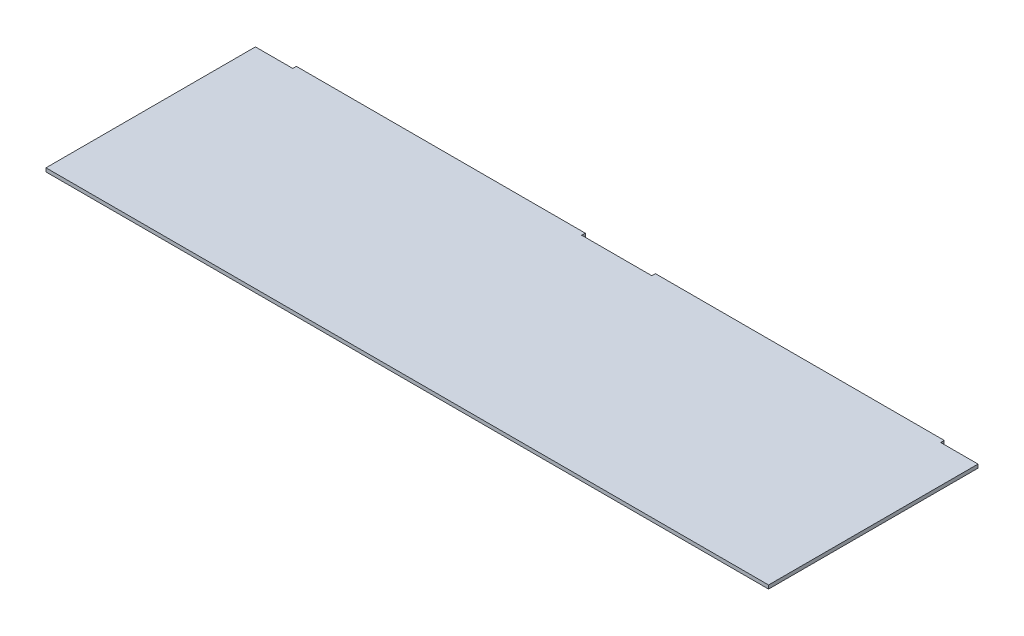
SolidWorks part; units mm, degrees
material "6061-T6 (SS)"
ref_plane "X-Y Datum" through (0, 0, 0) normal (0, 0, 1) x (1, 0, 0)
ref_plane "X-Z Datum" through (0, 0, 0) normal (0, 1, 0) x (1, 0, 0)
ref_plane "Y-Z Datum" through (0, 0, 0) normal (1, 0, 0) x (0, 0, -1)
sketch "Sketch1" plane through (0, 0, 0) normal (0, 1, 0) x (1, 0, 0)
  line L1 (-317.6778, 92.075) -> (317.6778, 92.075)
  line L2 (-317.6778, 92.075) -> (-317.6778, -92.075)
  line L3 (-317.6778, -92.075) -> (317.6778, -92.075)
  line L4 (317.6778, 92.075) -> (317.6778, -92.075)
  line L5 (-317.6778, 92.075) -> (317.6778, -92.075) construction
  line L6 (-317.6778, -92.075) -> (317.6778, 92.075) construction
  point P0 (0, 0)
  dimension "D1" = 635.3556
  dimension "D2" = 184.15
extrude "Boss-Extrude1" add sketch "Sketch1" along normal mid plane 3.175
sketch "Sketch2" plane through (0, 0, -92.075) normal (0, 0, -1) x (-1, 0, 0)
  line L20 (-317.6778, -1.5875) -> (317.6778, -1.5875) construction
  line L21 (-284.8229, -1.5875) -> (-30.8229, -1.5875)
  line L22 (30.8229, -1.5875) -> (284.8229, -1.5875)
  line L40 (30.8229, -1.5875) -> (30.8229, 1.5875)
  line L41 (30.8229, 1.5875) -> (284.8229, 1.5875)
  line L42 (284.8229, 1.5875) -> (284.8229, -1.5875)
  line L56 (-284.8229, -1.5875) -> (-284.8229, 1.5875)
  line L57 (-284.8229, 1.5875) -> (-30.8229, 1.5875)
  line L58 (-30.8229, 1.5875) -> (-30.8229, -1.5875)
extrude "Boss-Extrude2" add sketch "Sketch2" along normal blind 3.175
